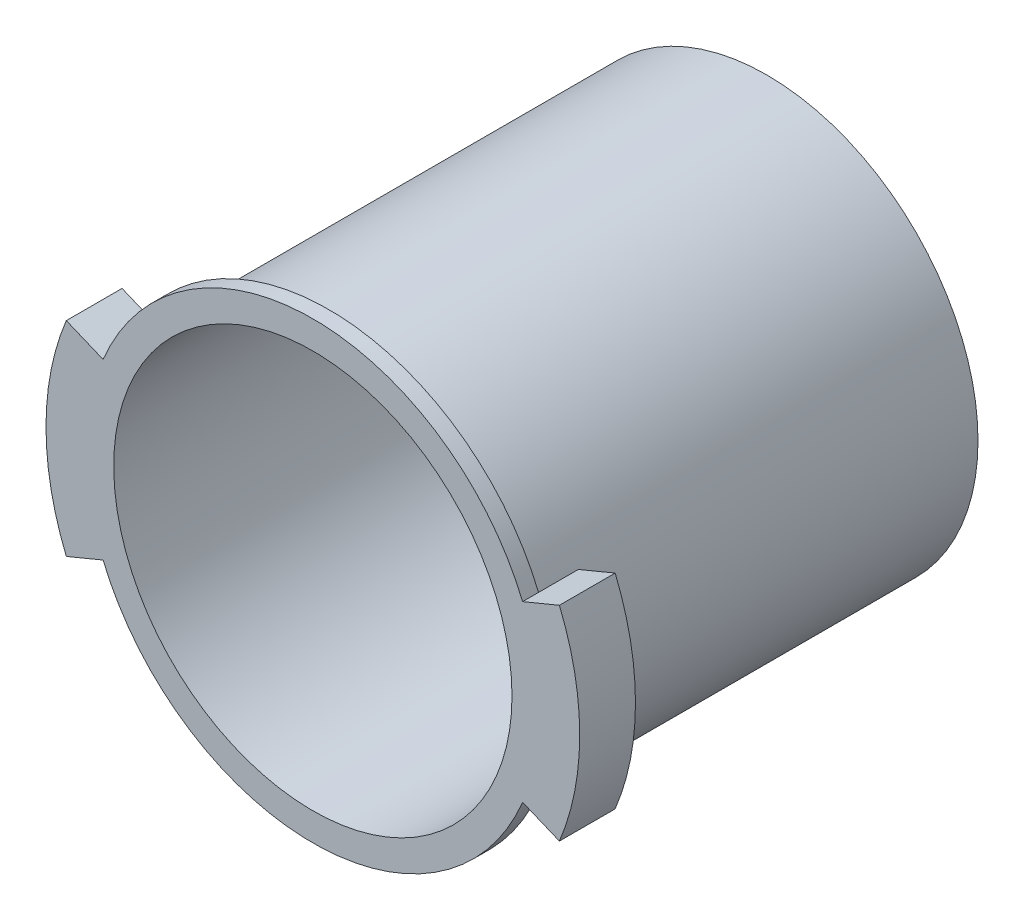
SolidWorks part; units mm, degrees
ref_plane "Plan de face" through (0, 0, 0) normal (0, 0, 1) x (1, 0, 0)
ref_plane "Plan de dessus" through (0, 0, 0) normal (0, 1, 0) x (1, 0, 0)
ref_plane "Plan de droite" through (0, 0, 0) normal (1, 0, 0) x (0, 0, -1)
sketch "Sketch1" plane through (0, 0, 0) normal (0, 0, 1) x (1, 0, 0)
  circle A0 centre (0, 0) radius 26.5
  circle A1 centre (0, 0) radius 25
  dimension "D1" = 53
  dimension "D2" = 50
extrude "Boss-Extrude1" add sketch "Sketch1" along normal blind 55
sketch "Sketch2" plane through (0, 0, 55) normal (0, 0, 1) x (1, 0, 0)
  line L0 (-26.3306, 10.9065) -> (-30.95, 12.8199)
  line L1 (-26.3306, -10.9065) -> (-30.95, -12.8199)
  line L2 (-11.5, 0) -> (-33.5, 0) construction
  line L3 (0, 0) -> (0, -47.3646) construction
  line L4 (26.3306, -10.9065) -> (30.95, -12.8199)
  line L5 (26.3306, 10.9065) -> (30.95, 12.8199)
  arc A0 (-30.95, 12.8199) -> (-30.95, -12.8199) centre (0, 0) ccw
  arc A2 (30.95, -12.8199) -> (30.95, 12.8199) centre (0, 0) ccw
  arc A4 (-26.3306, -10.9065) -> (26.3306, -10.9065) centre (0, 0) ccw
  arc A5 (26.3306, 10.9065) -> (-26.3306, 10.9065) centre (0, 0) ccw
  circle A6 centre (0, 0) radius 25
  dimension "D1" = 67
  dimension "D3" = 45
extrude "Boss-Extrude2" add sketch "Sketch2" along normal blind 2
sketch "Sketch3" plane through (0, 0, 55) normal (0, 0, -1) x (-1, 0, 0)
  line L8 (-26.3306, 10.9065) -> (-30.95, 12.8199)
  line L9 (-30.95, -12.8199) -> (-26.3306, -10.9065)
  line L10 (26.3306, -10.9065) -> (30.95, -12.8199)
  line L11 (30.95, 12.8199) -> (26.3306, 10.9065)
  line L12 (-26.3306, 10.9065) -> (-30.95, 12.8199)
  line L13 (-30.95, -12.8199) -> (-26.3306, -10.9065)
  line L14 (26.3306, -10.9065) -> (30.95, -12.8199)
  line L15 (30.95, 12.8199) -> (26.3306, 10.9065)
  circle A4 centre (0, 0) radius 28.5
  circle A5 centre (0, 0) radius 26.5
  arc A8 (26.3306, 10.9065) -> (-26.3306, 10.9065) centre (0, 0) ccw
  arc A9 (-30.95, 12.8199) -> (-30.95, -12.8199) centre (0, 0) ccw
  arc A10 (-26.3306, -10.9065) -> (26.3306, -10.9065) centre (0, 0) ccw
  arc A11 (30.95, -12.8199) -> (30.95, 12.8199) centre (0, 0) ccw
  arc A12 (26.3306, 10.9065) -> (-26.3306, 10.9065) centre (0, 0) ccw
  arc A13 (-30.95, 12.8199) -> (-30.95, -12.8199) centre (0, 0) ccw
  arc A14 (-26.3306, -10.9065) -> (26.3306, -10.9065) centre (0, 0) ccw
  arc A15 (30.95, -12.8199) -> (30.95, 12.8199) centre (0, 0) ccw
  line M11 (-26.3306, 10.9065) -> (-30.95, 12.8199)
  arc M12 (-30.95, 12.8199) -> (-30.95, -12.8199) centre (0, 0) ccw
  line M13 (-30.95, -12.8199) -> (-26.3306, -10.9065)
  line M15 (26.3306, -10.9065) -> (30.95, -12.8199)
  arc M16 (30.95, -12.8199) -> (30.95, 12.8199) centre (0, 0) ccw
  line M17 (30.95, 12.8199) -> (26.3306, 10.9065)
  dimension "D2" = 53
  dimension "D1" = 0
extrude "Boss-Extrude3" add sketch "Sketch3" along normal blind 5 contours A4 M11 M12 M13 | A4 M15 M16 M17
ref_plane "Plane1" through (0, 0, 20) normal (0, 0, -1) x (-1, 0, 0)
sketch "Sketch5" plane through (0, 0, 20) normal (0, 0, -1) x (-1, 0, 0)
  line L1 (-10, -30) -> (10, -30)
  line L2 (-10, -30) -> (-10, -20)
  line L3 (-10, -20) -> (10, -20)
  line L4 (10, -30) -> (10, -20)
  dimension "D1" = 20
  dimension "D2" = 10
  dimension "D3" = 20
  dimension "D4" = 10
extrude "Cut-Extrude1" cut sketch "Sketch5" along normal blind 68
ref_plane "Plane2" through (0, 0, 15) normal (0, 0, -1) x (-1, 0, 0)
sketch "Sketch7" plane through (0, 0, 15) normal (0, 0, -1) x (-1, 0, 0)
  line L0 (21.9317, -12) -> (17.5, -12)
  line L1 (-17.8467, -12) -> (-8.1631, -12)
  line L2 (24.4949, -5) -> (17.5, -5)
  line L3 (0, -8.5) -> (0, 0) construction
  line L4 (-21.9317, -12) -> (-17.5, -12)
  line L5 (-24.4949, -5) -> (-17.5, -5)
  circle A0 centre (0, -8.5) radius 14 construction
  arc A1 (10, -22.9129) -> (-10, -22.9129) centre (0, 0) ccw construction
  arc A2 (17.5, -5) -> (17.5, -12) centre (17.5, -8.5) ccw
  arc A3 (21.9317, -12) -> (24.4949, -5) centre (0, 0) ccw
  arc A4 (-17.5, -5) -> (-17.5, -12) centre (-17.5, -8.5) cw
  arc A5 (-21.9317, -12) -> (-24.4949, -5) centre (0, 0) cw
  dimension "D3" = 28
  dimension "D5" = 17.5
  dimension "D1" = 12
  dimension "D2" = 8.5
  dimension "D4" = 5
extrude "Boss-Extrude4" add sketch "Sketch7" against normal blind 2 contours A5 L4 A4 L5 | L0 A3 L2 A2
